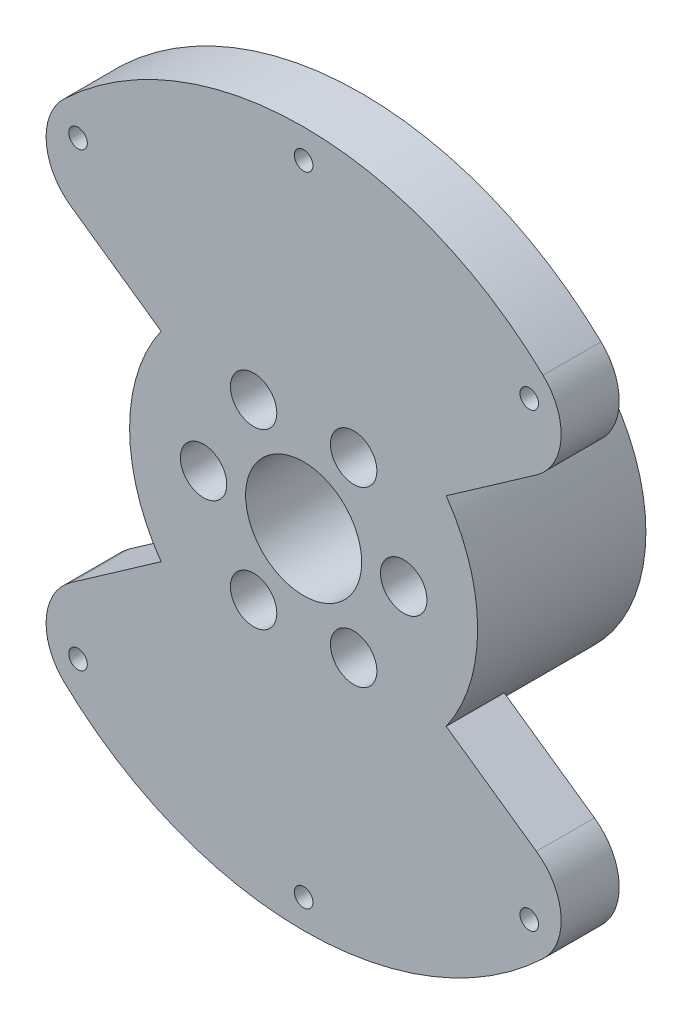
SolidWorks part; units mm, degrees
ref_plane "前视基准面" through (0, 0, 0) normal (0, 0, 1) x (1, 0, 0)
ref_plane "上视基准面" through (0, 0, 0) normal (0, 1, 0) x (1, 0, 0)
ref_plane "右视基准面" through (0, 0, 0) normal (1, 0, 0) x (0, 0, -1)
sketch "草图1" plane through (0, 0, 0) normal (0, 0, 1) x (1, 0, 0)
  circle A0 centre (0, 0) radius 30
extrude "凸台-拉伸1" add sketch "草图1" along normal blind 24
sketch "草图6" plane through (0, 0, 24) normal (0, 0, 1) x (1, 0, 0)
  circle A0 centre (0, 0) radius 10
extrude "切除-拉伸5" cut sketch "草图6" against normal blind 26
sketch "草图7" plane through (0, 0, 24) normal (0, 0, 1) x (1, 0, 0)
  circle A0 centre (17.25, 0) radius 2.2
  circle A1 centre (8.625, -14.9389) radius 2.2
  circle A2 centre (-8.625, -14.9389) radius 2.2
  circle A3 centre (-17.25, 0) radius 2.2
  circle A4 centre (-8.625, 14.9389) radius 2.2
  circle A5 centre (8.625, 14.9389) radius 2.2
  point P15 (0, 0)
  dimension "D1" = 4.4
  dimension "D2" = 17.25
  dimension "D3" = 6
extrude "切除-拉伸6" cut sketch "草图7" against normal through all
sketch "草图8" plane through (0, 0, 24) normal (0, 0, 1) x (1, 0, 0)
  circle A0 centre (-8.625, 14.9389) radius 2.2 construction
  circle A1 centre (0, 0) radius 30
  circle A2 centre (0, 0) radius 30
  circle A3 centre (-8.625, 14.9389) radius 2.2
  circle A4 centre (8.625, 14.9389) radius 2.2 construction
  circle A5 centre (17.25, 0) radius 2.2 construction
  circle A6 centre (8.625, -14.9389) radius 2.2 construction
  circle A7 centre (-8.625, -14.9389) radius 2.2 construction
  circle A8 centre (-17.25, 0) radius 2.2 construction
  circle A9 centre (8.625, 14.9389) radius 2.2
  circle A10 centre (17.25, 0) radius 2.2
  circle A11 centre (8.625, -14.9389) radius 2.2
  circle A12 centre (-8.625, -14.9389) radius 2.2
  circle A13 centre (-17.25, 0) radius 2.2
  circle A14 centre (-8.625, 14.9389) radius 4
  circle A15 centre (8.625, 14.9389) radius 4
  circle A16 centre (17.25, 0) radius 4
  circle A17 centre (8.625, -14.9389) radius 4
  circle A18 centre (-8.625, -14.9389) radius 4
  circle A19 centre (-17.25, 0) radius 4
  circle M2 centre (17.25, 0) radius 2.2
  circle M3 centre (8.625, 14.9389) radius 2.2
  circle M4 centre (-8.625, 14.9389) radius 2.2
  circle M5 centre (-17.25, 0) radius 2.2
  circle M6 centre (-8.625, -14.9389) radius 2.2
  circle M7 centre (8.625, -14.9389) radius 2.2
  dimension "D2" = 8
  dimension "D3" = 8
  dimension "D4" = 8
  dimension "D5" = 8
  dimension "D6" = 8
  dimension "D7" = 8
  dimension "D1" = 0
extrude "切除-拉伸7" cut sketch "草图8" against normal offset from surface (19 mm away) 5 contours A14 M4 | A19 M5 | A15 M3 | A16 M2 | A17 M7 | A18 M6 up to face at (19.45, 0, 0)
sketch "草图9" plane through (0, 0, 24) normal (0, 0, 1) x (1, 0, 0)
  circle A0 centre (0, 0) radius 60
  circle A1 centre (0, 0) radius 30
  circle A2 centre (0, 0) radius 30
  dimension "D2" = 120
  dimension "D1" = 0
extrude "凸台-拉伸2" add sketch "草图9" against normal blind 10
sketch "草图10" plane through (0, 0, 14) normal (0, 0, -1) x (-1, 0, 0)
  line L0 (39.7277, 42.0139) -> (36.6047, 41.1771)
  line L1 (3.2332, 55) -> (1.6166, 57.8)
  line L2 (1.6166, 57.8) -> (-1.6166, 57.8)
  line L3 (-1.6166, 57.8) -> (-3.2332, 55)
  line L4 (-3.2332, 55) -> (-1.6166, 52.2)
  line L5 (-1.6166, 52.2) -> (1.6166, 52.2)
  line L6 (1.6166, 52.2) -> (3.2332, 55)
  line L7 (42.0139, 39.7277) -> (39.7277, 42.0139)
  line L8 (36.6047, 41.1771) -> (35.7679, 38.0541)
  line L9 (35.7679, 38.0541) -> (38.0541, 35.7679)
  line L10 (38.0541, 35.7679) -> (41.1771, 36.6047)
  line L11 (41.1771, 36.6047) -> (42.0139, 39.7277)
  line L12 (57.8, 1.6166) -> (55, 3.2332)
  line L13 (57.8, -1.6166) -> (57.8, 1.6166)
  line L14 (55, 3.2332) -> (52.2, 1.6166)
  line L15 (52.2, 1.6166) -> (52.2, -1.6166)
  line L16 (52.2, -1.6166) -> (55, -3.2332)
  line L17 (55, -3.2332) -> (57.8, -1.6166)
  line L18 (42.0139, -39.7277) -> (41.1771, -36.6047)
  line L19 (39.7277, -42.0139) -> (42.0139, -39.7277)
  line L20 (41.1771, -36.6047) -> (38.0541, -35.7679)
  line L21 (38.0541, -35.7679) -> (35.7679, -38.0541)
  line L22 (35.7679, -38.0541) -> (36.6047, -41.1771)
  line L23 (36.6047, -41.1771) -> (39.7277, -42.0139)
  line L24 (1.6166, -57.8) -> (3.2332, -55)
  line L25 (-1.6166, -57.8) -> (1.6166, -57.8)
  line L26 (3.2332, -55) -> (1.6166, -52.2)
  line L27 (1.6166, -52.2) -> (-1.6166, -52.2)
  line L28 (-1.6166, -52.2) -> (-3.2332, -55)
  line L29 (-3.2332, -55) -> (-1.6166, -57.8)
  line L30 (-39.7277, -42.0139) -> (-36.6047, -41.1771)
  line L31 (-42.0139, -39.7277) -> (-39.7277, -42.0139)
  line L32 (-36.6047, -41.1771) -> (-35.7679, -38.0541)
  line L33 (-35.7679, -38.0541) -> (-38.0541, -35.7679)
  line L34 (-38.0541, -35.7679) -> (-41.1771, -36.6047)
  line L35 (-41.1771, -36.6047) -> (-42.0139, -39.7277)
  line L36 (-57.8, -1.6166) -> (-55, -3.2332)
  line L37 (-57.8, 1.6166) -> (-57.8, -1.6166)
  line L38 (-55, -3.2332) -> (-52.2, -1.6166)
  line L39 (-52.2, -1.6166) -> (-52.2, 1.6166)
  line L40 (-52.2, 1.6166) -> (-55, 3.2332)
  line L41 (-55, 3.2332) -> (-57.8, 1.6166)
  line L42 (-42.0139, 39.7277) -> (-41.1771, 36.6047)
  line L43 (-39.7277, 42.0139) -> (-42.0139, 39.7277)
  line L44 (-41.1771, 36.6047) -> (-38.0541, 35.7679)
  line L45 (-38.0541, 35.7679) -> (-35.7679, 38.0541)
  line L46 (-35.7679, 38.0541) -> (-36.6047, 41.1771)
  line L47 (-36.6047, 41.1771) -> (-39.7277, 42.0139)
  circle A0 centre (0, 0) radius 55
  circle A1 centre (0, 0) radius 60
  circle A2 centre (0, 0) radius 60
  circle A3 centre (0, 55) radius 2.8 construction
  circle A4 centre (38.8909, 38.8909) radius 2.8 construction
  circle A5 centre (55, 0) radius 2.8 construction
  circle A6 centre (38.8909, -38.8909) radius 2.8 construction
  circle A7 centre (0, -55) radius 2.8 construction
  circle A8 centre (-38.8909, -38.8909) radius 2.8 construction
  circle A9 centre (-55, 0) radius 2.8 construction
  circle A10 centre (-38.8909, 38.8909) radius 2.8 construction
  point P71 (0, 0)
  dimension "D2" = 110
  dimension "D3" = 5.6
  dimension "D4" = 8
  dimension "D1" = 0
extrude "切除-拉伸8" cut sketch "草图10" against normal blind 3 contours A0 L46 L47 L43 L42 L44 | L46 A0 L44 L45 | A0 L40 L41 L37 L36 L38 | L40 A0 L38 L39 | A0 L34 L35 L31 L30 L32 | L34 A0 L32 L33 | A0 L28 L29 L25 L24 L26 | L28 A0 L26 L27 | A0 L22 L23 L19 L18 L20 | L22 A0 L20 L21 | A0 L10 L11 L7 L0 L8 | L10 A0 L8 L9 | A0 L16 L17 L13 L12 L14 | L16 A0 L14 L15 | A0 L6 L1 L2 L3 L4 | L6 A0 L4 L5
sketch "草图11" plane through (0, 0, 14) normal (0, 0, -1) x (-1, 0, 0)
  line L0 (-3.2332, 55) -> (-1.6166, 52.2) construction
  line L1 (-1.6166, 57.8) -> (-3.2332, 55) construction
  line L2 (1.6166, 57.8) -> (-1.6166, 57.8) construction
  line L3 (3.2332, 55) -> (1.6166, 57.8) construction
  line L4 (1.6166, 52.2) -> (3.2332, 55) construction
  line L5 (-1.6166, 52.2) -> (1.6166, 52.2) construction
  line L6 (-3.2332, 55) -> (-1.6166, 52.2)
  line L7 (-1.6166, 57.8) -> (-3.2332, 55)
  line L8 (1.6166, 57.8) -> (-1.6166, 57.8)
  line L9 (3.2332, 55) -> (1.6166, 57.8)
  line L10 (1.6166, 52.2) -> (3.2332, 55)
  line L11 (-1.6166, 52.2) -> (1.6166, 52.2)
  line L12 (-1.6166, 57.8) -> (1.6166, 52.2) construction
  line L13 (1.6166, 57.8) -> (-1.6166, 52.2) construction
  circle A0 centre (0, 55) radius 1.6
  circle A1 centre (0, 0) radius 60
  circle A2 centre (0, 0) radius 60
  circle A3 centre (38.8909, 38.8909) radius 1.6
  circle A4 centre (55, 0) radius 1.6
  circle A5 centre (38.8909, -38.8909) radius 1.6
  circle A6 centre (0, -55) radius 1.6
  circle A7 centre (-38.8909, -38.8909) radius 1.6
  circle A8 centre (-55, 0) radius 1.6
  circle A9 centre (-38.8909, 38.8909) radius 1.6
  point P27 (0, 0)
  dimension "D2" = 3.2
  dimension "D1" = 0
  dimension "D3" = 8
extrude "切除-拉伸9" cut sketch "草图11" against normal through all contours A0 | A9 | A8 | A7 | A6 | A5 | A4 | A3
sketch "草图12" plane through (0, 0, 24) normal (0, 0, 1) x (1, 0, 0)
  line L0 (-51.8, 0) -> (-59.821, 4.6309)
  line L1 (-51.8, 0) -> (-59.821, -4.6309)
  line L2 (-60, 0) -> (60, 0)
  line L3 (0, 60) -> (0, -60)
  line L4 (51.8, 0) -> (59.821, 4.6309)
  line L5 (51.8, 0) -> (59.821, -4.6309)
  circle A0 centre (-55, 0) radius 1.6 construction
  circle A1 centre (0, 0) radius 60
  circle A2 centre (0, 0) radius 60
  dimension "D2" = 60
  dimension "D3" = 30
  dimension "D1" = 0
extrude "切除-拉伸11" cut sketch "草图12" against normal blind 10
sketch "草图13" plane through (0, 0, 24) normal (0, 0, 1) x (1, 0, 0)
  line L0 (0, 0) -> (-49.1491, 34.4146)
  line L1 (-55, 0) -> (55, 0)
  line L2 (0, 0) -> (-49.1491, -34.4146)
  line L3 (0, 60) -> (0, -60)
  line L4 (-59.821, 4.6309) -> (-54.2, 1.3856)
  line L5 (-54.2, -1.3856) -> (-59.821, -4.6309)
  line L6 (59.821, -4.6309) -> (54.2, -1.3856)
  line L7 (54.2, 1.3856) -> (59.821, 4.6309)
  line L8 (-59.821, 4.6309) -> (-54.2, 1.3856)
  line L9 (-54.2, -1.3856) -> (-59.821, -4.6309)
  line L10 (59.821, -4.6309) -> (54.2, -1.3856)
  line L11 (54.2, 1.3856) -> (59.821, 4.6309)
  line L12 (0, 0) -> (49.1491, -34.4146)
  line L13 (0, 0) -> (49.1491, 34.4146)
  circle A0 centre (0, 0) radius 30
  arc A4 (-54.2, -1.3856) -> (-54.2, 1.3856) centre (-55, 0) ccw
  arc A5 (-59.821, -4.6309) -> (59.821, -4.6309) centre (0, 0) ccw
  arc A6 (54.2, 1.3856) -> (54.2, -1.3856) centre (55, 0) ccw
  arc A7 (59.821, 4.6309) -> (-59.821, 4.6309) centre (0, 0) ccw
  arc A8 (-54.2, -1.3856) -> (-54.2, 1.3856) centre (-55, 0) ccw
  arc A9 (-59.821, -4.6309) -> (59.821, -4.6309) centre (0, 0) ccw
  arc A10 (54.2, 1.3856) -> (54.2, -1.3856) centre (55, 0) ccw
  arc A11 (59.821, 4.6309) -> (-59.821, 4.6309) centre (0, 0) ccw
  line M13 (-59.821, 4.6309) -> (-54.2, 1.3856)
  arc M14 (-54.2, 1.3856) -> (-54.2, -1.3856) centre (-55, 0) cw
  line M15 (-54.2, -1.3856) -> (-59.821, -4.6309)
  arc M16 (-59.821, -4.6309) -> (59.821, -4.6309) centre (0, 0) ccw
  line M17 (59.821, -4.6309) -> (54.2, -1.3856)
  arc M18 (54.2, -1.3856) -> (54.2, 1.3856) centre (55, 0) cw
  line M19 (54.2, 1.3856) -> (59.821, 4.6309)
  arc M20 (59.821, 4.6309) -> (-59.821, 4.6309) centre (0, 0) ccw
  dimension "D2" = 60
  dimension "D3" = 35
  dimension "D4" = 35
  dimension "D1" = 0
extrude "切除-拉伸12" cut sketch "草图13" against normal blind 10 contours A0 L0 L1 M20 M13 M14 | A0 L1 L2 M14 M15 M16 | A0 L1 L13 M18 M19 M20 | A0 L12 L1 M16 M17 M18
fillet "圆角1" radius 10 4 edges at (49.1491, 34.4146, 19) (49.1491, -34.4146, 19) (-49.1491, -34.4146, 19) (-49.1491, 34.4146, 19)
sketch "草图14" plane through (0, 0, 0) normal (0, 0, -1) x (-1, 0, 0)
  circle A1 centre (0, 0) radius 10
  circle A2 centre (0, 0) radius 10
  circle A3 centre (8.625, 14.9389) radius 2.2
  circle A4 centre (8.625, 14.9389) radius 2.2
  circle A5 centre (17.25, 0) radius 2.2
  circle A6 centre (17.25, 0) radius 2.2
  circle A7 centre (8.625, -14.9389) radius 2.2
  circle A8 centre (8.625, -14.9389) radius 2.2
  circle A9 centre (-8.625, -14.9389) radius 2.2
  circle A10 centre (-8.625, -14.9389) radius 2.2
  circle A11 centre (-8.625, 14.9389) radius 2.2
  circle A12 centre (-8.625, 14.9389) radius 2.2
  circle A13 centre (-17.25, 0) radius 2.2
  circle A14 centre (-17.25, 0) radius 2.2
  circle A15 centre (0, 0) radius 30
  circle A16 centre (0, 0) radius 30
  dimension "D1" = 0
  dimension "D2" = 0
  dimension "D3" = 0
  dimension "D4" = 0
  dimension "D5" = 0
  dimension "D6" = 0
  dimension "D7" = 0
  dimension "D8" = 0
extrude "凸台-拉伸3" add sketch "草图14" along normal blind 5
move or copy body "实体-移动/复制1" [suppressed] bodies to move or copy 119 parameters "D1"=0, "D2"=0, "D3"=0
move or copy body "实体-移动/复制2" [suppressed] bodies to move or copy 120 parameters "D1"=0, "D2"=0, "D3"=0
move or copy body "实体-移动/复制3" [suppressed] bodies to move or copy 121 parameters "D1"=0, "D2"=0, "D3"=0
move or copy body "实体-移动/复制4" [suppressed] bodies to move or copy 122 parameters "D1"=0, "D2"=0, "D3"=0
